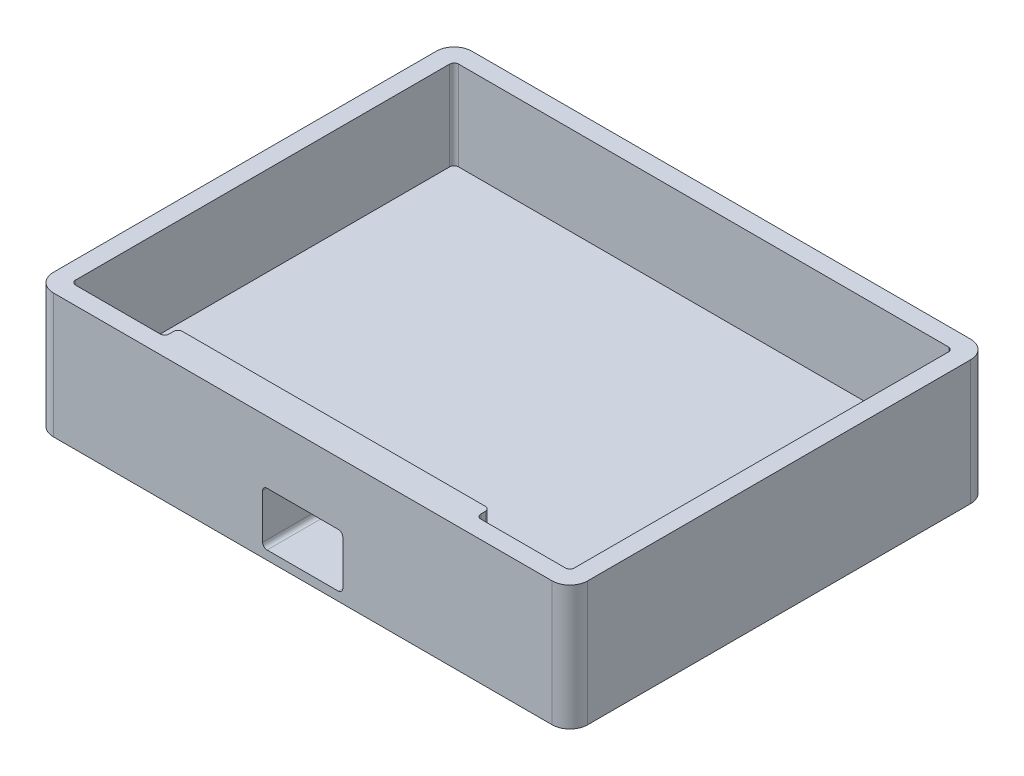
SolidWorks part; units mm, degrees
ref_plane "Front Plane" through (0, 0, 0) normal (0, 0, 1) x (1, 0, 0)
ref_plane "Top Plane" through (0, 0, 0) normal (0, 1, 0) x (1, 0, 0)
ref_plane "Right Plane" through (0, 0, 0) normal (1, 0, 0) x (0, 0, -1)
sketch "Sketch1" plane through (0, 0, 0) normal (0, 1, 0) x (1, 0, 0)
  line L1 (-30, -23.5) -> (30, -23.5)
  line L2 (-30, -23.5) -> (-30, 23.5)
  line L3 (-30, 23.5) -> (30, 23.5)
  line L4 (30, -23.5) -> (30, 23.5)
  line L5 (-30, -23.5) -> (30, 23.5) construction
  line L6 (-30, 23.5) -> (30, -23.5) construction
  point P0 (0, 0)
  dimension "D1" = 60
  dimension "D2" = 47
extrude "Boss-Extrude1" add sketch "Sketch1" along normal blind 4
sketch "Sketch2" plane through (0, 4, 0) normal (0, 1, 0) x (1, 0, 0)
  line L1 (-28, -21.5) -> (28, -21.5)
  line L2 (-28, -21.5) -> (-28, 21.5)
  line L3 (-28, 21.5) -> (28, 21.5)
  line L4 (28, -21.5) -> (28, 21.5)
  line L5 (-28, -21.5) -> (28, 21.5) construction
  line L6 (-28, 21.5) -> (28, -21.5) construction
  line L7 (-30, -23.5) -> (30, -23.5)
  line L8 (-30, -23.5) -> (-30, 23.5)
  line L9 (-30, 23.5) -> (30, 23.5)
  line L10 (30, -23.5) -> (30, 23.5)
  line L11 (-30, -23.5) -> (30, 23.5) construction
  line L12 (-30, 23.5) -> (30, -23.5) construction
  point P0 (0, 0)
  point P6 (0, 0)
  dimension "D1" = 2
  dimension "D2" = 2
extrude "Boss-Extrude2" add sketch "Sketch2" along normal blind 10
sketch "Sketch4" plane through (0, 0, 21.5) normal (0, 0, -1) x (-1, 0, 0)
  line L0 (0, 0) -> (0, 14) construction
  line L1 (-30, 14) -> (30, 14) construction
  line L2 (-30, 0) -> (30, 0) construction
  line L3 (-17.5, 2) -> (17.5, 2)
  line L4 (-17.5, 2) -> (-17.5, 14)
  line L5 (-17.5, 14) -> (17.5, 14)
  line L6 (17.5, 2) -> (17.5, 14)
  line L7 (-17.5, 2) -> (17.5, 14) construction
  line L8 (-17.5, 14) -> (17.5, 2) construction
  line L9 (-30, 14) -> (-30, 0) construction
  point P5 (0, 8)
  dimension "D1" = 2
  dimension "D2" = 12.5
extrude "Boss-Extrude3" add sketch "Sketch4" along normal blind 1.5
sketch "Sketch5" plane through (0, 4, 0) normal (0, 1, 0) x (1, 0, 0)
  line L0 (0, 23.5) -> (0, -23.5) construction
  line L1 (30, 23.5) -> (-30, 23.5) construction
  line L2 (-30, -23.5) -> (30, -23.5) construction
  line L4 (-4.5, -15.5) -> (4.5, -15.5)
  line L5 (-4.5, -15.5) -> (-4.5, -23.5)
  line L6 (-4.5, -23.5) -> (4.5, -23.5)
  line L7 (4.5, -15.5) -> (4.5, -23.5)
  line L8 (-4.5, -15.5) -> (4.5, -23.5) construction
  line L9 (-4.5, -23.5) -> (4.5, -15.5) construction
  point P6 (0, -19.5)
  dimension "D1" = 8
  dimension "D2" = 9
extrude "Cut-Extrude1" cut sketch "Sketch5" against normal blind 3 and the other way blind 3
fillet "Fillet1" radius 2 4 edges at (30, 7, -23.5) (30, 7, 23.5) (-30, 7, 23.5) (-30, 7, -23.5)
fillet "Fillet2" radius 0.5 8 edges at (-17.5, 9, 20) (17.5, 9, 20) (17.5, 9, 21.5) (-17.5, 9, 21.5) (-28, 9, -21.5) (28, 9, -21.5) (28, 9, 21.5) (-28, 9, 21.5)
fillet "Fillet3" radius 0.5 4 edges at (4.5, 1, 19.5) (-4.5, 1, 19.5) (-4.5, 7, 21.75) (4.5, 7, 21.75)
